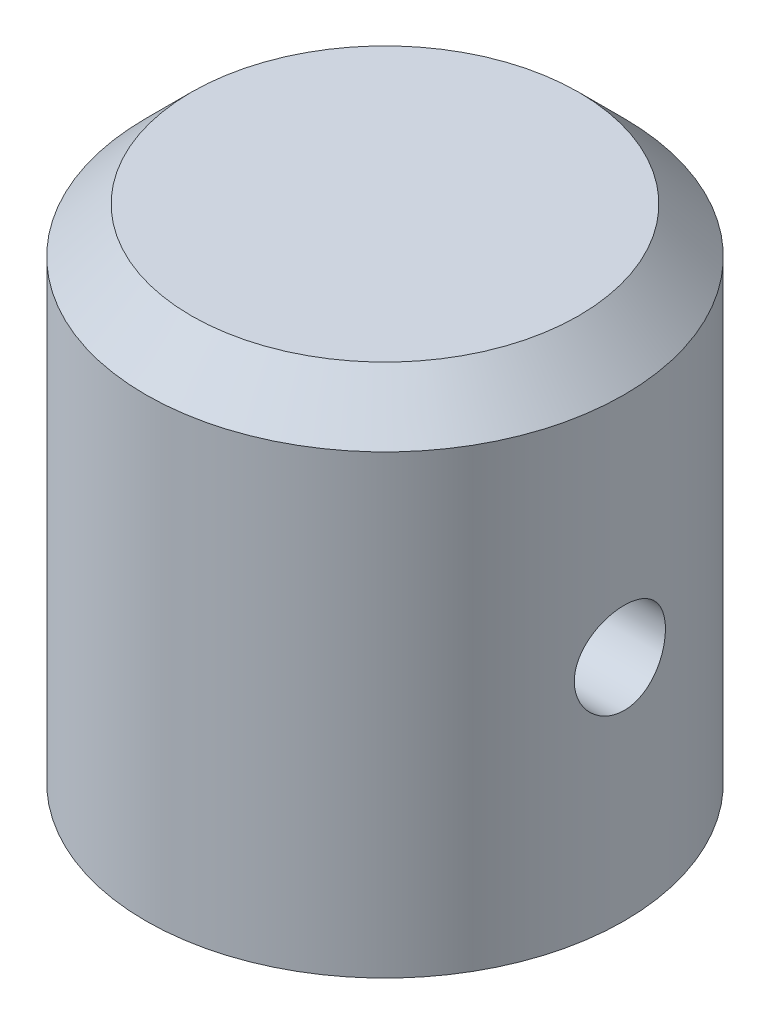
SolidWorks part; units mm, degrees
ref_plane "Piano frontale" through (0, 0, 0) normal (0, 0, 1) x (1, 0, 0)
ref_plane "Piano superiore" through (0, 0, 0) normal (0, 1, 0) x (1, 0, 0)
ref_plane "Piano destro" through (0, 0, 0) normal (1, 0, 0) x (0, 0, -1)
sketch "Schizzo2" plane through (0, 0, 0) normal (0, 1, 0) x (1, 0, 0)
  circle A0 centre (0, 0) radius 10.5
  dimension "D1" = 21
extrude "Estrusione-Estrusione1" add sketch "Schizzo2" along normal blind 22
sketch "Schizzo3" plane through (0, 0, 0) normal (0, -1, 0) x (1, 0, 0)
  line L1 (-2.8609, 7.5) -> (2.8609, 7.5)
  line L2 (-5, 5.3609) -> (-5, -5.3609)
  line L3 (-2.8609, -7.5) -> (2.8609, -7.5)
  line L4 (5, 5.3609) -> (5, -5.3609)
  line L5 (-5, 7.5) -> (5, -7.5) construction
  line L6 (-5, -7.5) -> (5, 7.5) construction
  arc A0 (-5, -5.3609) -> (-2.8609, -7.5) centre (-2.8609, -5.3609) ccw
  arc A1 (2.8609, -7.5) -> (5, -5.3609) centre (2.8609, -5.3609) ccw
  arc A2 (5, 5.3609) -> (2.8609, 7.5) centre (2.8609, 5.3609) ccw
  arc A3 (-5, 5.3609) -> (-2.8609, 7.5) centre (-2.8609, 5.3609) cw
  point P0 (0, 0)
  dimension "D3" = 2.1391
  dimension "D1" = 10
  dimension "D2" = 15
extrude "Taglio-Estrusione1" cut sketch "Schizzo3" against normal blind 17 contours L1 A2 L4 A1 L3 A0 L2 A3
chamfer "Smusso1" distance 2 angle 45 1 edges at (0, 22, 10.5)
sketch "Schizzo4" plane through (0, 0, 0) normal (1, 0, 0) x (0, 0, -1)
  line L1 (-10.5, 0) -> (10.5, 0)
  line L2 (-10.5, 0) -> (-10.5, 22)
  line L3 (-10.5, 22) -> (10.5, 22)
  line L4 (10.5, 0) -> (10.5, 22)
  circle A0 centre (0, 10) radius 2
  point P7 (0, 0)
  point P8 (0, 0)
  dimension "D1" = 4
  dimension "D2" = 10
extrude "Taglio-Estrusione2" cut sketch "Schizzo4" against normal through all both and the other way through all contours A0
sketch "Schizzo5" plane through (0, 0, 0) normal (0, -1, 0) x (1, 0, 0)
  circle A0 centre (7, 0) radius 0.9
  point P2 (0, 0)
  dimension "D1" = 1.8
  dimension "D2" = 7
extrude "Taglio-Estrusione3" cut sketch "Schizzo5" against normal blind 19 and the other way through all contours A0
